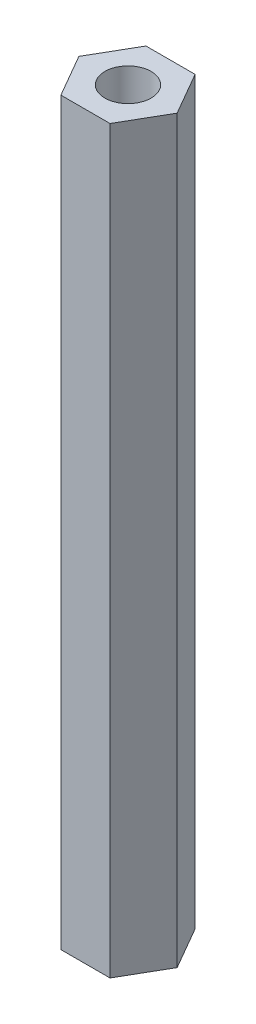
SolidWorks part; units mm, degrees
ref_plane "前视基准面" through (0, 0, 0) normal (0, 0, 1) x (1, 0, 0)
ref_plane "上视基准面" through (0, 0, 0) normal (0, 1, 0) x (1, 0, 0)
ref_plane "右视基准面" through (0, 0, 0) normal (1, 0, 0) x (0, 0, -1)
sketch "草图1" plane through (0, 0, 0) normal (0, 1, 0) x (1, 0, 0)
  line L1 (1.3279, -2.3) -> (2.6558, 0)
  line L2 (2.6558, 0) -> (1.3279, 2.3)
  line L3 (1.3279, 2.3) -> (-1.3279, 2.3)
  line L4 (-1.3279, 2.3) -> (-2.6558, 0)
  line L5 (-2.6558, 0) -> (-1.3279, -2.3)
  line L6 (-1.3279, -2.3) -> (1.3279, -2.3)
  circle A0 centre (0, 0) radius 2.3 construction
  dimension "D1" = 4.6
extrude "凸台-拉伸1" add sketch "草图1" along normal mid plane 40
hole_wizard "M3 螺纹孔1" positions "3D草图2" profile "草图3" tap size "M3" standard "GB" end condition up to next
sketch3d "3D草图2"
  point P0 (0, 0, 0)
  point P3 (0, 0, 0)
  point P5 (0, 20, 0)
sketch "草图3" plane through (0, 20, 0) normal (1, 0, 0) x (0, 0, 1)
  line L0 (0, 0) -> (0, 40.001)
  line L1 (0, 40.001) -> (1.25, 40.001)
  line L2 (1.25, 40.001) -> (1.25, 0)
  line L5 (1.25, 0) -> (0, 0)
  line L11 (0, -6.35) -> (0, 107.95) construction
  dimension "通孔螺纹孔钻头直径" = 2.5
  dimension "通孔螺纹孔钻头深度" = 40.001
cosmetic thread "孔螺蚊线1" parameters "D2"=3
cosmetic thread "孔螺蚊线2" parameters "D2"=3
cosmetic thread "孔螺蚊线3" parameters "D2"=3
